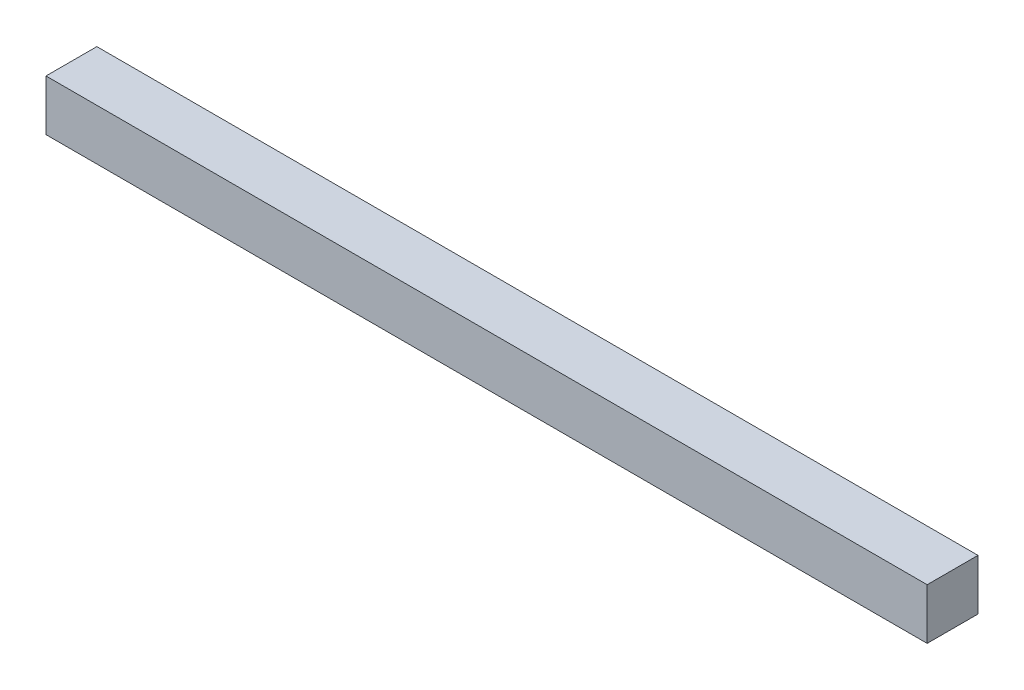
SolidWorks part; units mm, degrees
ref_plane "Front Plane" through (0, 0, 0) normal (0, 0, 1) x (1, 0, 0)
ref_plane "Top Plane" through (0, 0, 0) normal (0, 1, 0) x (1, 0, 0)
ref_plane "Right Plane" through (0, 0, 0) normal (1, 0, 0) x (0, 0, -1)
sketch "Sketch1" plane through (0, 0, 0) normal (0, 0, 1) x (1, 0, 0)
  line L1 (-0.0717, 15.0065) -> (259.9283, 15.0065)
  line L2 (-0.0717, 15.0065) -> (-0.0717, 0.0065)
  line L3 (-0.0717, 0.0065) -> (259.9283, 0.0065)
  line L4 (259.9283, 15.0065) -> (259.9283, 0.0065)
  dimension "D1" = 15
  dimension "D2" = 260
extrude "Boss-Extrude3" add sketch "Sketch1" against normal blind 15 contours L2 L1 L4 L3
